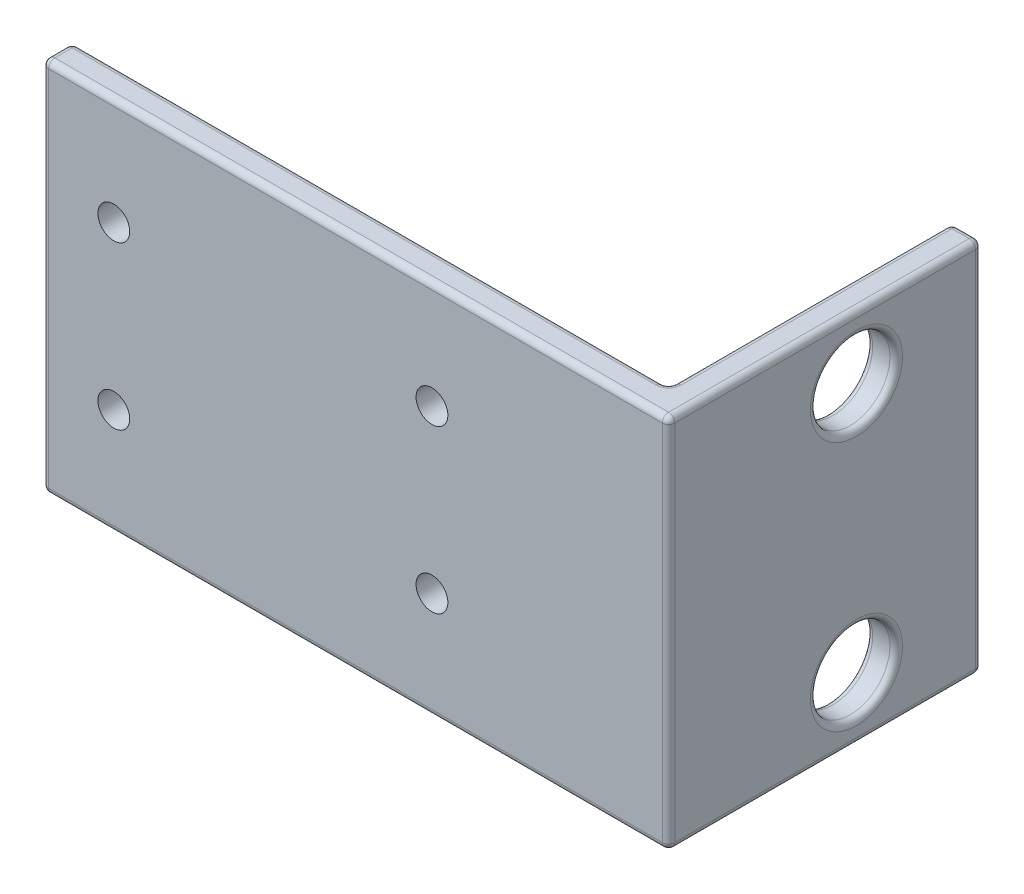
SolidWorks part; units mm, degrees
ref_plane "Front Plane" through (0, 0, 0) normal (0, 0, 1) x (1, 0, 0)
ref_plane "Top Plane" through (0, 0, 0) normal (0, 1, 0) x (1, 0, 0)
ref_plane "Right Plane" through (0, 0, 0) normal (1, 0, 0) x (0, 0, -1)
sketch "Sketch1" plane through (0, 0, 0) normal (0, 1, 0) x (1, 0, 0)
  line L0 (0, 0) -> (0, 22.6188)
  line L1 (0, 22.6188) -> (2.3813, 22.6188)
  line L2 (2.3813, 22.6188) -> (2.3813, -2.3812)
  line L3 (2.3813, -2.3812) -> (-47.6187, -2.3813)
  line L4 (-47.6187, -2.3813) -> (-47.6187, 0)
  line L5 (-47.6187, 0) -> (0, 0)
  dimension "D1" = 2.3813
  dimension "D2" = 25
  dimension "D3" = 50
extrude "Boss-Extrude1" add sketch "Sketch1" along normal blind 30
sketch "Sketch2" plane through (0, 0, 2.3812) normal (0, 0, 1) x (1, 0, 0)
  line L4 (-47.6187, 0) -> (2.3813, 0)
  line L5 (2.3813, 0) -> (2.3813, 30)
  line L6 (2.3813, 30) -> (-47.6187, 30)
  line L7 (-47.6187, 30) -> (-47.6187, 0)
  line L8 (-47.6187, 0) -> (2.3813, 0) construction
  line L9 (2.3813, 0) -> (2.3813, 30) construction
  line L10 (2.3813, 30) -> (-47.6187, 30) construction
  line L11 (-47.6187, 30) -> (-47.6187, 0) construction
  circle A0 centre (-41.91, 8.523) radius 1.27 construction
  circle A1 centre (-41.91, 8.523) radius 1.27
  circle A2 centre (-16.51, 8.523) radius 1.27 construction
  circle A3 centre (-16.51, 8.523) radius 1.27
  circle A4 centre (-16.51, 21.477) radius 1.27 construction
  circle A5 centre (-16.51, 21.477) radius 1.27
  circle A6 centre (-41.91, 21.477) radius 1.27 construction
  circle A7 centre (-41.91, 21.477) radius 1.27
  dimension "D1" = 0
extrude "Cut-Extrude1" cut sketch "Sketch2" against normal through all
sketch "Sketch3" plane through (2.3813, 0, 0) normal (1, 0, 0) x (0, 0, -1)
  line L4 (-2.3812, 0) -> (22.6188, 0)
  line L5 (22.6188, 0) -> (22.6188, 30)
  line L6 (22.6188, 30) -> (-2.3812, 30)
  line L7 (-2.3812, 30) -> (-2.3812, 0)
  line L8 (-2.3812, 0) -> (22.6188, 0) construction
  line L9 (22.6188, 0) -> (22.6188, 30) construction
  line L10 (22.6188, 30) -> (-2.3812, 30) construction
  line L11 (-2.3812, 30) -> (-2.3812, 0) construction
  circle A0 centre (12.6188, 25) radius 3.175
  circle A1 centre (12.6188, 5) radius 3.175
  point P2 (12.6188, 25)
  point P4 (12.6188, 5)
  dimension "D5" = 6.35
  dimension "D2" = 20
  dimension "D3" = 5
  dimension "D4" = 15
  dimension "D1" = 0
extrude "Cut-Extrude2" cut sketch "Sketch3" against normal through all
fillet "Fillet1" radius 0.5 26 edges at (-47.6187, 15, 2.3813) (-47.6187, 0, 1.1906) (-22.6187, 0, 2.3812) (2.3813, 15, 2.3812) (2.3813, 0, -10.1188) (2.3813, 5, -15.7938) (2.3813, 25, -15.7938) (2.3813, 15, -22.6188) (1.1906, 0, -22.6188) (1.1906, 30, -22.6188) (2.3813, 30, -10.1188) (-22.6187, 30, 2.3812) (-47.6187, 30, 1.1906) (0, 15, -22.6188) (0, 30, -11.3094) (0, 0, -11.3094) (0, 5, -15.7938) (0, 25, -15.7938) (0, 15, 0) (-23.8094, 30, 0) (-47.6187, 15, 0) (-23.8094, 0, 0) (-40.64, 8.523, 0) (-15.24, 8.523, 0) (-15.24, 21.477, 0) (-40.64, 21.477, 0)
